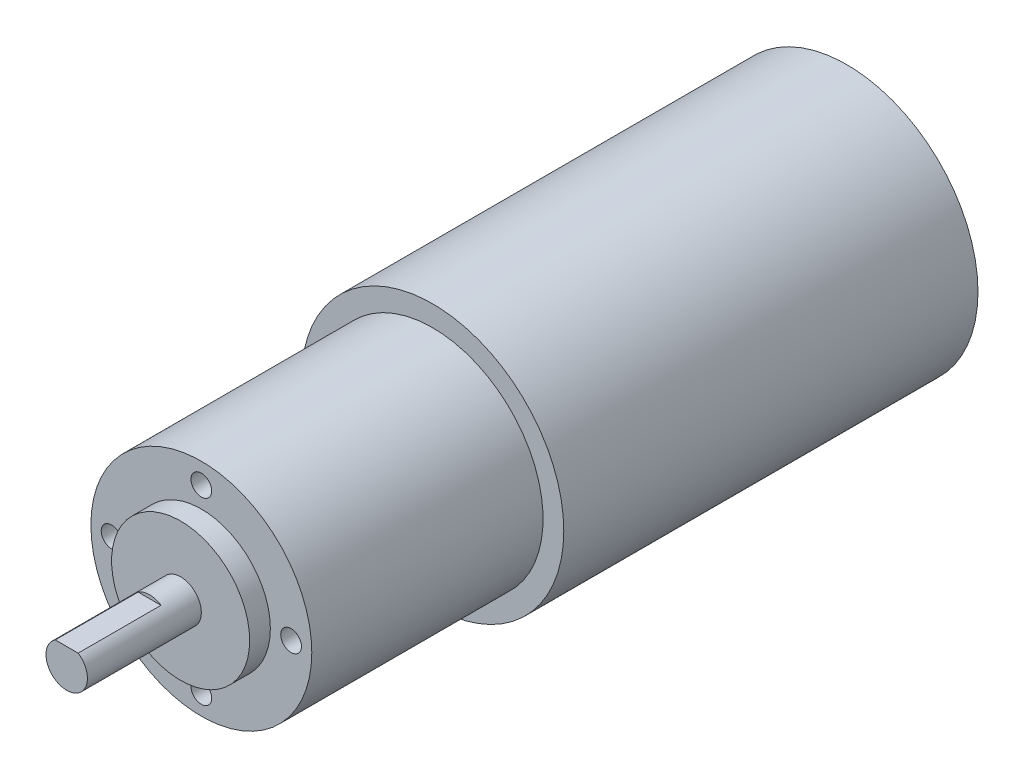
SolidWorks part; units mm, degrees
ref_plane "正面" through (0, 0, 0) normal (0, 0, 1) x (1, 0, 0)
ref_plane "平面" through (0, 0, 0) normal (0, 1, 0) x (1, 0, 0)
ref_plane "右側面" through (0, 0, 0) normal (1, 0, 0) x (0, 0, -1)
sketch "ｽｹｯﾁ1" plane through (0, 0, 0) normal (0, 0, 1) x (1, 0, 0)
  circle A0 centre (0, 0) radius 16
  dimension "D1" = 32
extrude "ﾎﾞｽ - 押し出し1" add sketch "ｽｹｯﾁ1" along normal blind 33.5
sketch "ｽｹｯﾁ2" plane through (0, 0, 33.5) normal (0, 0, 1) x (1, 0, 0)
  circle A0 centre (0, 0) radius 10
  dimension "D1" = 20
extrude "ﾎﾞｽ - 押し出し2" add sketch "ｽｹｯﾁ2" along normal blind 3
sketch "ｽｹｯﾁ3" plane through (0, 0, 36.5) normal (0, 0, 1) x (1, 0, 0)
  circle A0 centre (0, 0) radius 3
  dimension "D1" = 6
extrude "ﾎﾞｽ - 押し出し3" add sketch "ｽｹｯﾁ3" along normal blind 16.5
sketch "ｽｹｯﾁ4" plane through (0, 0, 0) normal (0, 1, 0) x (1, 0, 0)
  line L0 (0, 0) -> (0, -50000) construction
  line L1 (-3, -53) -> (3, -53) construction
  line L2 (-4.6218, -41) -> (4.6218, -41)
  line L3 (-4.6218, -41) -> (-4.6218, -53)
  line L4 (-4.6218, -53) -> (4.6218, -53)
  line L5 (4.6218, -41) -> (4.6218, -53)
  line L6 (-4.6218, -41) -> (4.6218, -53) construction
  line L7 (-4.6218, -53) -> (4.6218, -41) construction
  point P3 (0, -47)
  dimension "D1" = 12
extrude "ｶｯﾄ - 押し出し1" cut sketch "ｽｹｯﾁ4" against normal blind 0.5 from offset 3
sketch "ｽｹｯﾁ5" plane through (0, 0, 0) normal (0, 0, -1) x (-1, 0, 0)
  circle A0 centre (0, 0) radius 19
  dimension "D1" = 38
extrude "ﾎﾞｽ - 押し出し4" add sketch "ｽｹｯﾁ5" along normal blind 60
sketch "ｽｹｯﾁ6" plane through (0, 0, 33.5) normal (0, 0, 1) x (1, 0, 0)
  line L0 (0, 0) -> (0, 50000) construction
  line L1 (0, 0) -> (50000, 0) construction
  circle A0 centre (0, 0) radius 13 construction
  circle A1 centre (0, 13) radius 1.5
  circle A2 centre (-13, 0) radius 1.5
  circle A3 centre (13, 0) radius 1.5
  circle A4 centre (0, -13) radius 1.5
  dimension "D1" = 3
  dimension "D2" = 26
extrude "ｶｯﾄ - 押し出し2" cut sketch "ｽｹｯﾁ6" against normal blind 5
